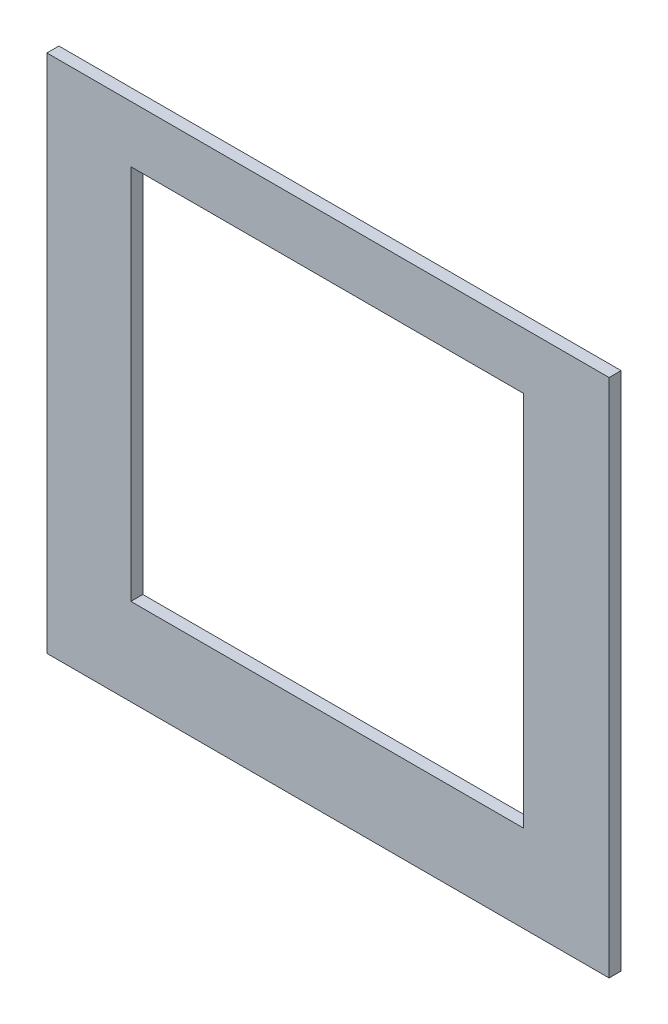
SolidWorks part; units mm, degrees
ref_plane "Front Plane" through (0, 0, 0) normal (0, 0, 1) x (1, 0, 0)
ref_plane "Top Plane" through (0, 0, 0) normal (0, 1, 0) x (1, 0, 0)
ref_plane "Right Plane" through (0, 0, 0) normal (1, 0, 0) x (0, 0, -1)
sketch "Sketch2" plane through (0, 0, 0) normal (0, 0, 1) x (1, 0, 0)
  line L0 (1904.5056, 1976.3577) -> (2796.9651, 1976.3577)
  line L1 (2796.9651, 1976.3577) -> (2796.9651, 2801.8577)
  line L2 (2796.9651, 2801.8577) -> (1904.5056, 2801.8577)
  line L3 (1904.5056, 2801.8577) -> (1904.5056, 1976.3577)
  line L4 (2037.7441, 2712.1002) -> (2661.1781, 2712.1002)
  line L5 (2661.1781, 2712.1002) -> (2661.1781, 2114.4931)
  line L6 (2661.1781, 2114.4931) -> (2037.7441, 2114.4931)
  line L7 (2037.7441, 2114.4931) -> (2037.7441, 2712.1002)
extrude "Boss-Extrude1" add sketch "Sketch2" along normal blind 19.05
